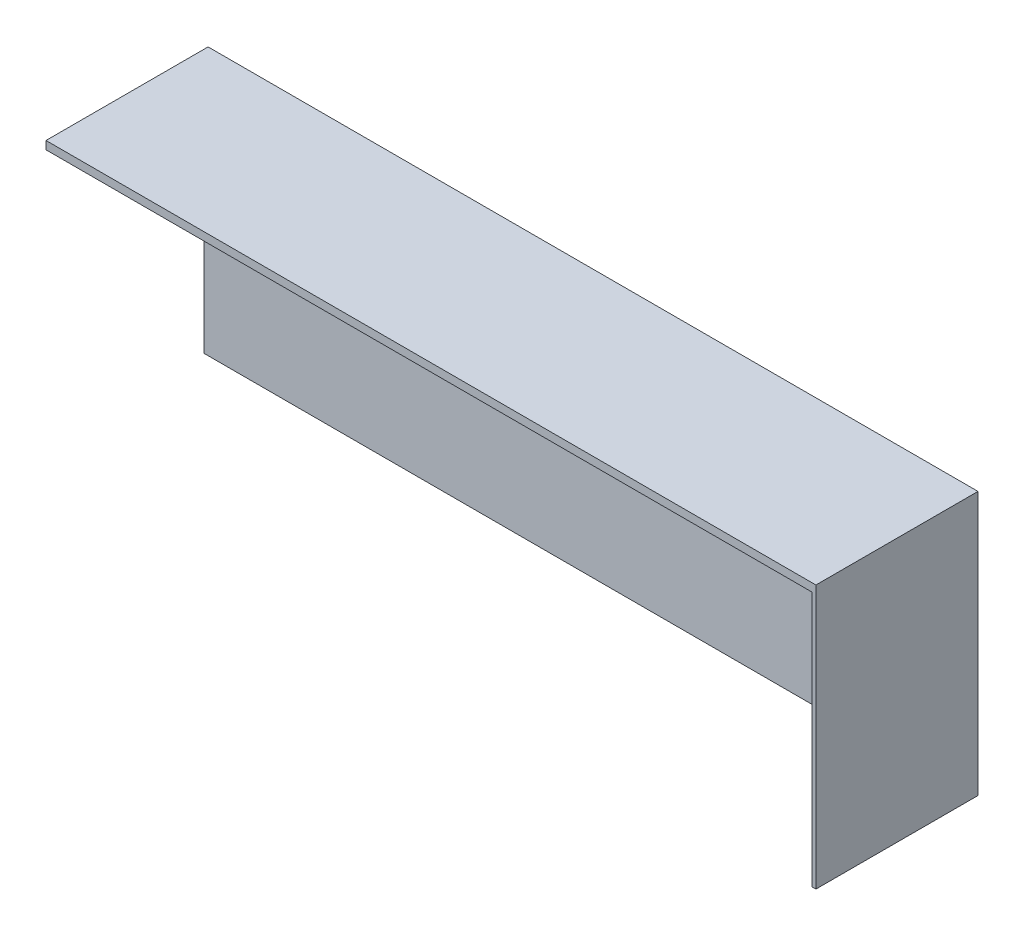
SolidWorks part; units mm, degrees
ref_plane "Front Plane" through (0, 0, 0) normal (0, 0, 1) x (1, 0, 0)
ref_plane "Top Plane" through (0, 0, 0) normal (0, 1, 0) x (1, 0, 0)
ref_plane "Right Plane" through (0, 0, 0) normal (1, 0, 0) x (0, 0, -1)
sketch "Sketch2" plane through (0, 0, 0) normal (0, 1, 0) x (1, 0, 0)
  line L0 (-1900, 0) -> (0, 0)
  line L1 (0, 0) -> (0, -400)
  line L2 (-1900, -10) -> (-10, -10)
  line L3 (-10, -10) -> (-10, -400)
  line L4 (-1900, 0) -> (-1900, -10)
  line L5 (-10, -400) -> (0, -400)
  point P7 (-1875.0599, -10)
  point P8 (0, -943.8181)
  dimension "D2" = 1900
  dimension "D3" = 400
  dimension "D1" = 10
extrude "Boss-Extrude1" add sketch "Sketch2" along normal up to surface (650 mm away)
sketch "Sketch3" plane through (0, 650, 0) normal (0, 1, 0) x (1, 0, 0)
  line L1 (0, 0) -> (-1900, 0)
  line L2 (0, 0) -> (0, -400)
  line L3 (0, -400) -> (-1900, -400)
  line L4 (-1900, 0) -> (-1900, -400)
extrude "Boss-Extrude2" add sketch "Sketch3" against normal blind 20
